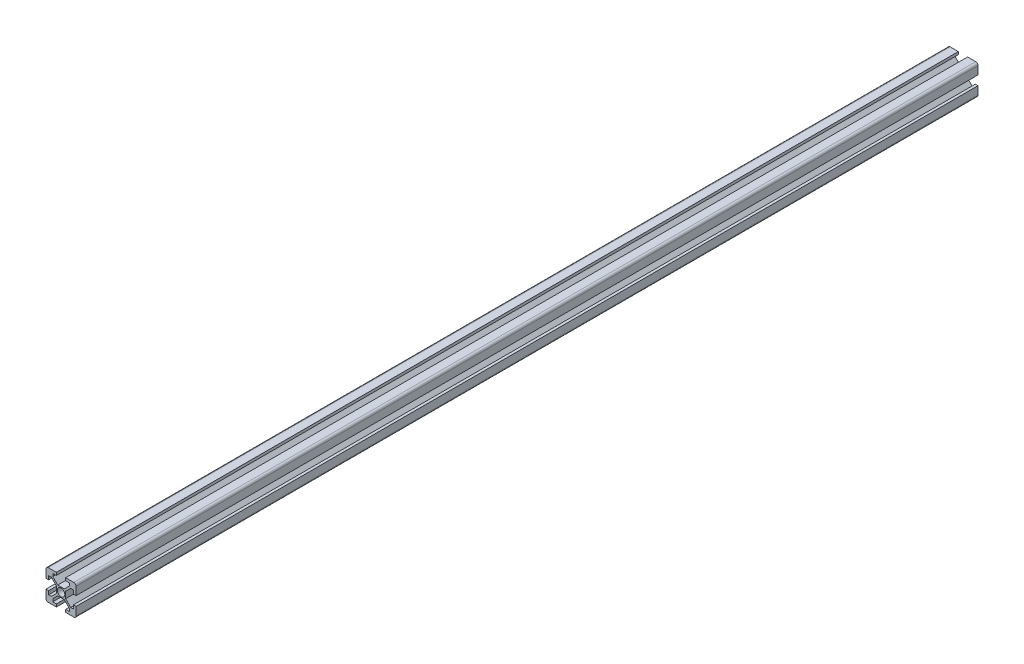
SolidWorks part; units mm, degrees
ref_plane "前视基准面" through (0, 0, 0) normal (0, 0, 1) x (1, 0, 0)
ref_plane "上视基准面" through (0, 0, 0) normal (0, 1, 0) x (1, 0, 0)
ref_plane "右视基准面" through (0, 0, 0) normal (1, 0, 0) x (0, 0, -1)
sketch "草图1" plane through (0, 0, 0) normal (0, 0, 1) x (1, 0, 0)
  line L0 (-10, -3.1) -> (-8.2, -3.1)
  line L1 (-8.5, 10) -> (8.5, 10)
  line L2 (-10, 8.5) -> (-10, -8.5)
  line L3 (-8.5, -10) -> (8.5, -10)
  line L4 (10, 8.5) -> (10, -8.5)
  line L5 (-10, 10) -> (10, -10) construction
  line L6 (-10, -10) -> (10, 10) construction
  line L7 (-3.0541, 3.1) -> (3.0541, 3.1)
  line L8 (-3.0541, 3.1) -> (-3.0541, -3.1)
  line L9 (-3.0541, -3.1) -> (3.0541, -3.1)
  line L10 (3.0541, 3.1) -> (3.0541, -3.1)
  line L11 (-3.0541, 3.1) -> (3.0541, -3.1) construction
  line L12 (-3.0541, -3.1) -> (3.0541, 3.1) construction
  line L13 (-8.2, -3.1) -> (-8.2, -5.5)
  line L14 (-8.2, -5.5) -> (-6.3971, -5.5)
  line L15 (-6.3971, -5.5) -> (-3.0541, -2.1571)
  line L16 (-5.5, 6.3971) -> (-2.1571, 3.0541)
  line L17 (-5.5, 8.2) -> (-5.5, 6.3971)
  line L18 (-3.1, 8.2) -> (-5.5, 8.2)
  line L19 (-3.1, 10) -> (-3.1, 8.2)
  line L20 (6.3971, 5.5) -> (3.0541, 2.1571)
  line L21 (8.2, 5.5) -> (6.3971, 5.5)
  line L22 (8.2, 3.1) -> (8.2, 5.5)
  line L23 (10, 3.1) -> (8.2, 3.1)
  line L24 (5.5, -6.3971) -> (2.1571, -3.0541)
  line L25 (5.5, -8.2) -> (5.5, -6.3971)
  line L26 (3.1, -8.2) -> (5.5, -8.2)
  line L27 (3.1, -10) -> (3.1, -8.2)
  line L28 (-3.1, -10) -> (-3.1, -8.2)
  line L29 (-3.1, -8.2) -> (-5.5, -8.2)
  line L30 (-5.5, -8.2) -> (-5.5, -6.3971)
  line L31 (-5.5, -6.3971) -> (-2.1571, -3.0541)
  line L32 (-8.2, 5.5) -> (-6.3971, 5.5)
  line L33 (-6.3971, 5.5) -> (-3.0541, 2.1571)
  line L34 (-8.2, 3.1) -> (-8.2, 5.5)
  line L35 (-10, 3.1) -> (-8.2, 3.1)
  line L36 (5.5, 8.2) -> (5.5, 6.3971)
  line L37 (5.5, 6.3971) -> (2.1571, 3.0541)
  line L38 (3.1, 8.2) -> (5.5, 8.2)
  line L39 (3.1, 10) -> (3.1, 8.2)
  line L40 (8.2, -5.5) -> (6.3971, -5.5)
  line L41 (6.3971, -5.5) -> (3.0541, -2.1571)
  line L42 (8.2, -3.1) -> (8.2, -5.5)
  line L43 (10, -3.1) -> (8.2, -3.1)
  circle A0 centre (0, 0) radius 2.5
  arc A1 (-10, 8.5) -> (-8.5, 10) centre (-8.5, 8.5) cw
  arc A2 (-10, -8.5) -> (-8.5, -10) centre (-8.5, -8.5) ccw
  arc A3 (8.5, 10) -> (10, 8.5) centre (8.5, 8.5) cw
  arc A4 (10, -8.5) -> (8.5, -10) centre (8.5, -8.5) cw
  point P0 (0, 0)
  point P20 (0, 0)
  point P26 (0, 0)
  point P32 (0, 0)
  point P38 (0, 0)
  point P60 (0, 0)
  dimension "D1" = 4
  dimension "D3" = 1.5
  dimension "D4" = 1.5
  dimension "D5" = 1.5
  dimension "D2" = 4
extrude "凸台-拉伸1" add sketch "草图1" along normal blind 600
